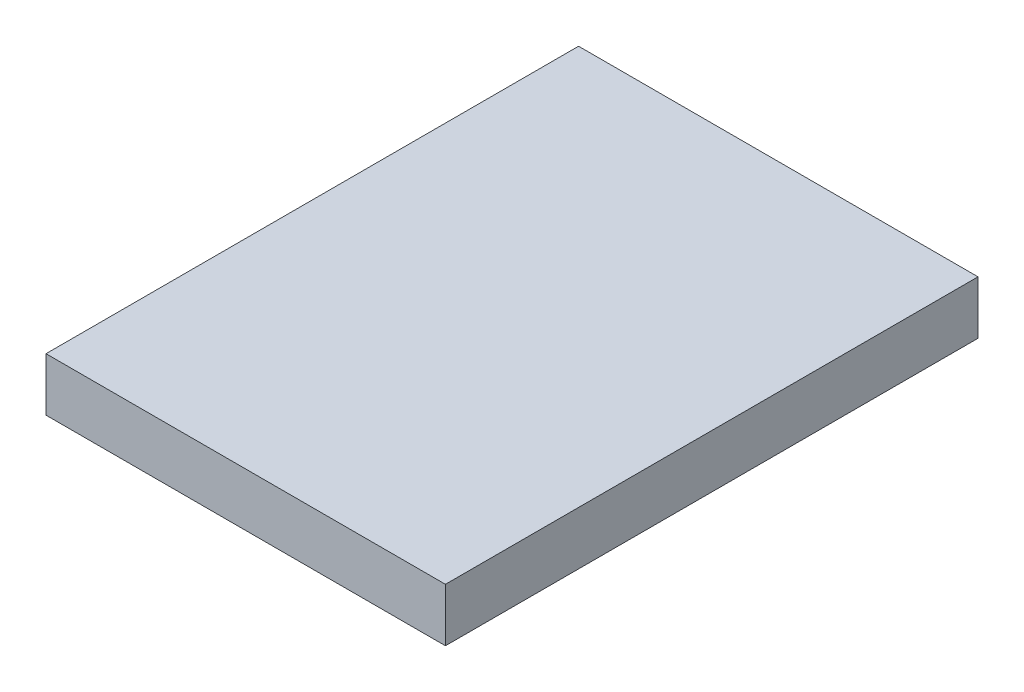
SolidWorks part; units mm, degrees
ref_plane "Front Plane" through (0, 0, 0) normal (0, 0, 1) x (1, 0, 0)
ref_plane "Top Plane" through (0, 0, 0) normal (0, 1, 0) x (1, 0, 0)
ref_plane "Right Plane" through (0, 0, 0) normal (1, 0, 0) x (0, 0, -1)
sketch "Sketch1" plane through (0, 0, 0) normal (0, 1, 0) x (1, 0, 0)
  line L1 (0, 0) -> (15000, 0)
  line L2 (0, 0) -> (0, -20000)
  line L3 (0, -20000) -> (15000, -20000)
  line L4 (15000, 0) -> (15000, -20000)
  line L5 (0, 0) -> (15000, -20000) construction
  line L6 (0, -20000) -> (15000, 0) construction
  point P4 (7500, -10000)
  dimension "D1" = 20000
  dimension "D2" = 15000
extrude "Boss-Extrude1" add sketch "Sketch1" along normal blind 2000
